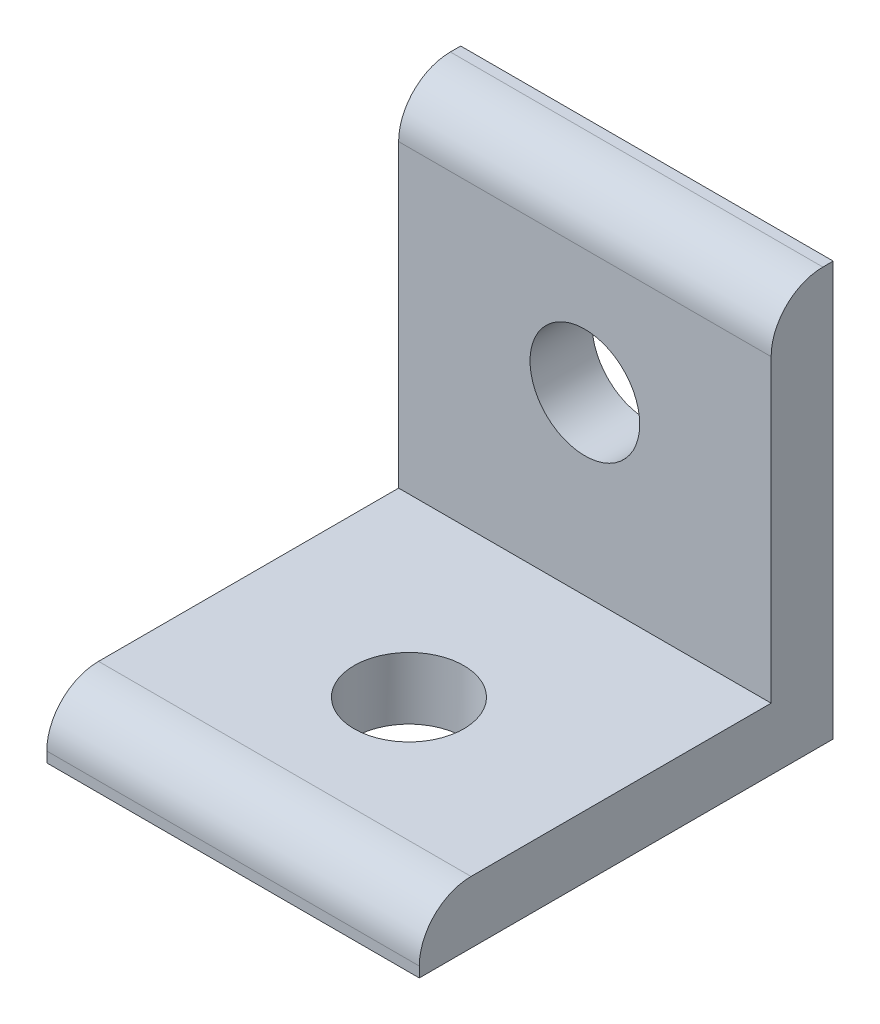
SolidWorks part; units mm, degrees
material "6061-T6 (SS)"
ref_plane "Front Plane" through (0, 0, 0) normal (0, 0, 1) x (1, 0, 0)
ref_plane "Top Plane" through (0, 0, 0) normal (0, 1, 0) x (1, 0, 0)
ref_plane "Right Plane" through (0, 0, 0) normal (1, 0, 0) x (0, 0, -1)
sketch "Sketch1" plane through (0, 0, 0) normal (0, 1, 0) x (1, 0, 0)
  line L0 (0, 0) -> (18, 0)
  line L1 (18, 0) -> (18, -20)
  line L2 (18, -20) -> (0, -20)
  line L3 (0, -20) -> (0, 0)
  dimension "D1" = 18
  dimension "D2" = 20
extrude "Boss-Extrude3" add sketch "Sketch1" along normal blind 3 contours L3 L0 L1 L2
sketch "Sketch4" plane through (0, 3, 0) normal (0, 1, 0) x (1, 0, 0)
  line L0 (0, 0) -> (18, 0)
  line L1 (18, 0) -> (18, -3)
  line L2 (18, 0) -> (18, -20) construction
  line L3 (18, -3) -> (0, -3)
  line L4 (0, -20) -> (0, 0) construction
  line L5 (0, -3) -> (0, 0)
  dimension "D1" = 3
extrude "Boss-Extrude4" add sketch "Sketch4" along normal blind 17
sketch "Sketch5" plane through (0, 3, 0) normal (0, 1, 0) x (1, 0, 0)
  line L0 (9, -3) -> (9, -20) construction
  line L1 (0, -3) -> (18, -3) construction
  line L2 (18, -20) -> (0, -20) construction
  circle A0 centre (9, -11.5) radius 2.65
  dimension "D1" = 5.3
extrude "Cut-Extrude1" cut sketch "Sketch5" against normal up to surface (3 mm away) up to face at (9, 0, 10)
sketch "Sketch6" plane through (0, 0, 3) normal (0, 0, 1) x (1, 0, 0)
  line L0 (9, 20) -> (9, 3) construction
  line L1 (0, 20) -> (18, 20) construction
  line L2 (0, 3) -> (18, 3) construction
  circle A0 centre (9, 11.5) radius 2.65
  dimension "D1" = 5.3
extrude "Cut-Extrude2" cut sketch "Sketch6" against normal up to surface (3 mm away) up to face at (9, 10, 0)
fillet "Fillet1" radius 2.5 2 edges at (9, 20, 3) (9, 3, 20)
